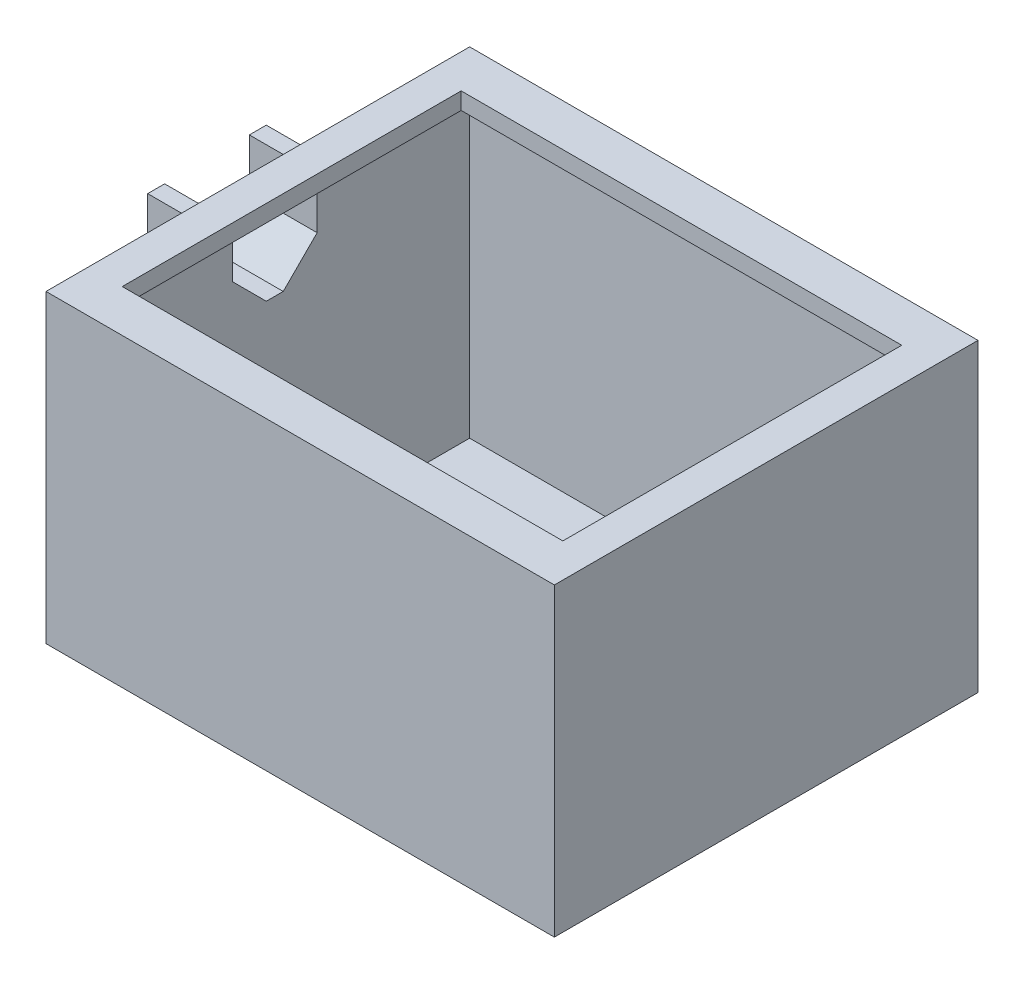
SolidWorks part; units mm, degrees
ref_plane "Front Plane" through (0, 0, 0) normal (0, 0, 1) x (1, 0, 0)
ref_plane "Top Plane" through (0, 0, 0) normal (0, 1, 0) x (1, 0, 0)
ref_plane "Right Plane" through (0, 0, 0) normal (1, 0, 0) x (0, 0, -1)
sketch "Sketch1" plane through (0, 0, 0) normal (0, 1, 0) x (1, 0, 0)
  line L1 (-30, 25) -> (30, 25)
  line L2 (-30, 25) -> (-30, -25)
  line L3 (-30, -25) -> (30, -25)
  line L4 (30, 25) -> (30, -25)
  line L5 (-30, 25) -> (30, -25) construction
  line L6 (-30, -25) -> (30, 25) construction
  point P0 (0, 0)
  dimension "D1" = 60
  dimension "D2" = 50
extrude "Boss-Extrude1" add sketch "Sketch1" along normal blind 40
shell "Shell1" thickness 2
sketch "Sketch2" plane through (0, 40, 0) normal (0, 1, 0) x (1, 0, 0)
  line L1 (-26, 20) -> (26, 20)
  line L2 (-26, 20) -> (-26, -20)
  line L3 (-26, -20) -> (26, -20)
  line L4 (26, 20) -> (26, -20)
  line L5 (-26, 20) -> (26, -20) construction
  line L6 (-26, -20) -> (26, 20) construction
  point P0 (0, 0)
  dimension "D1" = 52
  dimension "D2" = 40
extrude "Cut-Extrude1" cut sketch "Sketch2" against normal blind 10
chamfer "Chamfer1" distance 4 angle 45 4 edges at (0, 0, -25) (30, 0, 0) (0, 0, 25) (-30, 0, 0)
sketch "Sketch3" plane through (-30, 0, 0) normal (1, 0, 0) x (0, 0, -1)
  line L0 (-25, 40) -> (-25, 4) construction
  line L1 (5, 38) -> (-5, 38)
  line L2 (5, 38) -> (5, 28)
  line L3 (5, 28) -> (-5, 28)
  line L4 (-5, 38) -> (-5, 28)
  line L5 (5, 38) -> (-5, 28) construction
  line L6 (5, 28) -> (-5, 38) construction
  line L7 (25, 40) -> (-25, 40) construction
  point P0 (0, 33)
  dimension "D1" = 10
  dimension "D2" = 10
  dimension "D3" = 20
  dimension "D4" = 2
extrude "Cut-Extrude2" cut sketch "Sketch3" along normal blind 5
sketch "Sketch4" plane through (-30, 0, 0) normal (1, 0, 0) x (0, 0, -1)
  line L0 (-5, 38) -> (-7, 38)
  line L1 (-7, 38) -> (-7, 26)
  line L2 (-7, 26) -> (7, 26)
  line L3 (7, 26) -> (7, 38)
  line L4 (7, 38) -> (5, 38)
  line L5 (5, 38) -> (5, 28)
  line L6 (5, 28) -> (-5, 28)
  line L7 (-5, 28) -> (-5, 38)
  dimension "D1" = 14
  dimension "D2" = 12
extrude "Boss-Extrude2" add sketch "Sketch4" against normal blind 6
chamfer "Chamfer3" distance 5 angle 45 1 edges at (-30, 26, 0)
chamfer "Chamfer4" distance 4 angle 45 2 edges at (-32, 28, -5) (-32, 28, 5)
